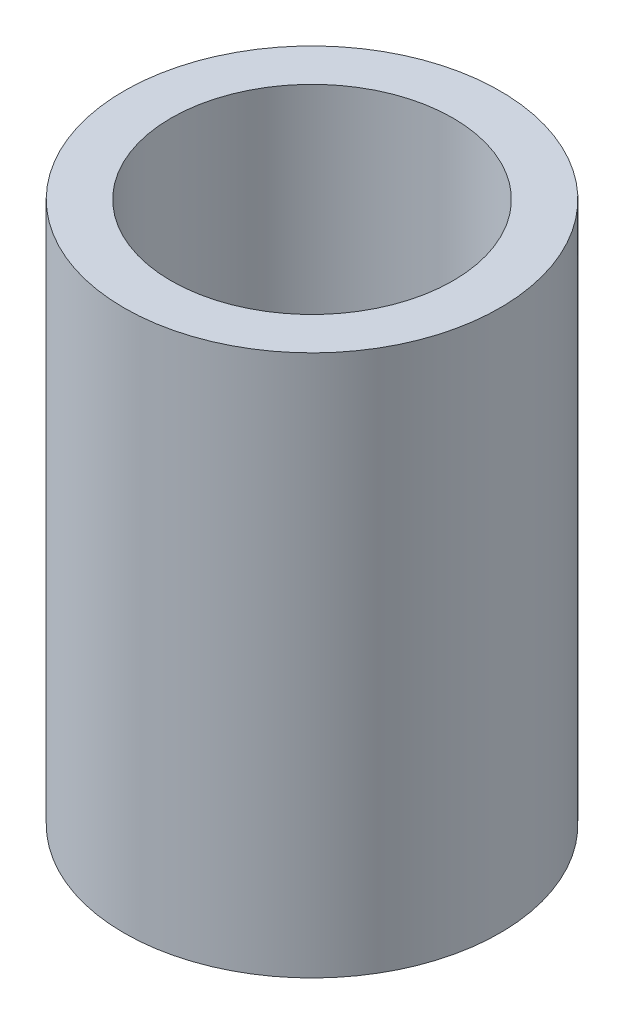
SolidWorks part; units mm, degrees
material "1060 Alloy"
ref_plane "Front Plane" through (0, 0, 0) normal (0, 0, 1) x (1, 0, 0)
ref_plane "Top Plane" through (0, 0, 0) normal (0, 1, 0) x (1, 0, 0)
ref_plane "Right Plane" through (0, 0, 0) normal (1, 0, 0) x (0, 0, -1)
sketch "Sketch1" plane through (0, 0, 0) normal (0, 1, 0) x (1, 0, 0)
  circle A0 centre (0, 0) radius 7.5
  circle A1 centre (0, 0) radius 10
  dimension "D1" = 15
  dimension "D2" = 20
extrude "Boss-Extrude1" add sketch "Sketch1" along normal blind 28.8
